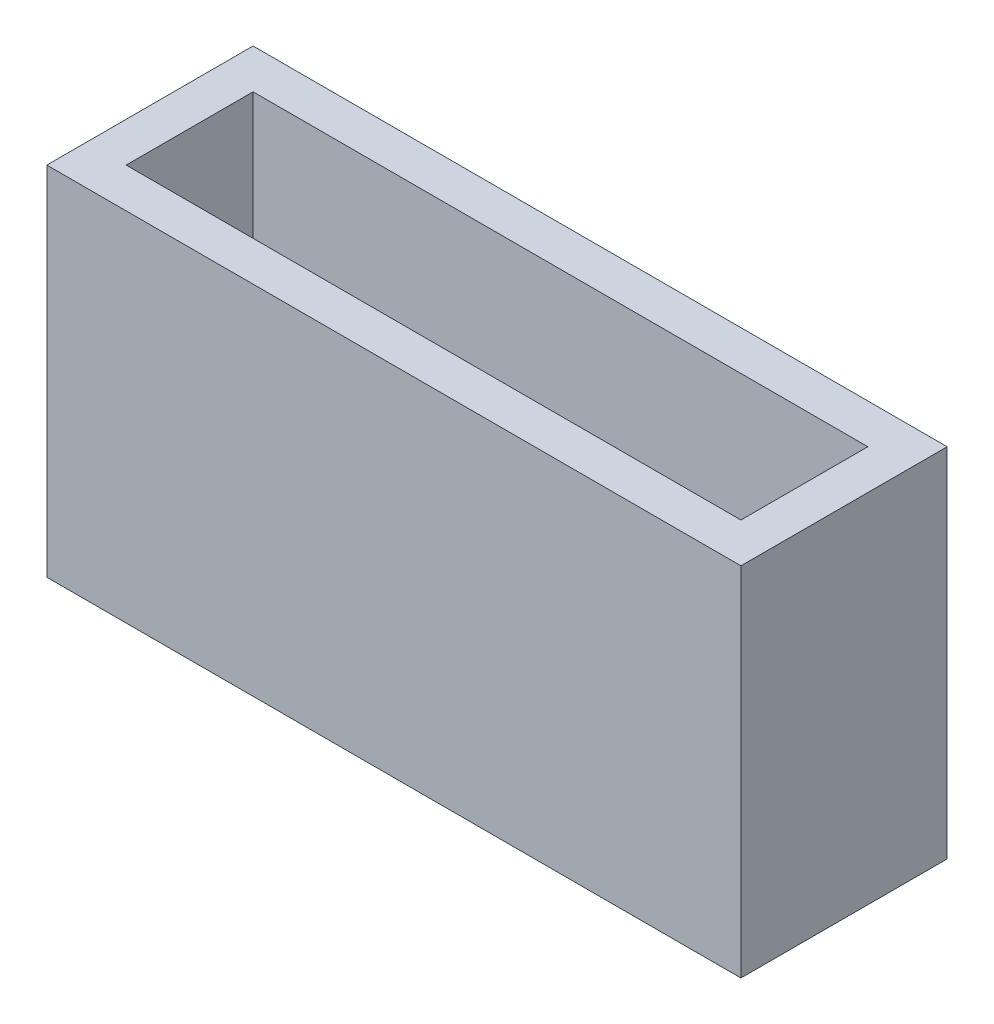
SolidWorks part; units mm, degrees
ref_plane "Front Plane" through (0, 0, 0) normal (0, 0, 1) x (1, 0, 0)
ref_plane "Top Plane" through (0, 0, 0) normal (0, 1, 0) x (1, 0, 0)
ref_plane "Right Plane" through (0, 0, 0) normal (1, 0, 0) x (0, 0, -1)
sketch "Sketch1" plane through (0, 0, 0) normal (0, 1, 0) x (1, 0, 0)
  line L0 (-1, -1) -> (-1, 4.2)
  line L1 (0, 0) -> (15.5, 0)
  line L2 (0, 0) -> (0, 3.2)
  line L3 (0, 3.2) -> (15.5, 3.2)
  line L4 (15.5, 0) -> (15.5, 3.2)
  line L5 (-1, 4.2) -> (16.5, 4.2)
  line L6 (16.5, -1) -> (16.5, 4.2)
  line L7 (-1, -1) -> (16.5, -1)
  dimension "D1" = 3.2
  dimension "D2" = 15.5
  dimension "D3" = 1
extrude "Boss-Extrude1" add sketch "Sketch1" along normal blind 7.5
sketch "Sketch2" plane through (0, 0, 0) normal (0, -1, 0) x (1, 0, 0)
  line L1 (-1, 1) -> (16.5, 1)
  line L2 (-1, 1) -> (-1, -4.2)
  line L3 (-1, -4.2) -> (16.5, -4.2)
  line L4 (16.5, 1) -> (16.5, -4.2)
extrude "Boss-Extrude2" add sketch "Sketch2" along normal blind 1.5
